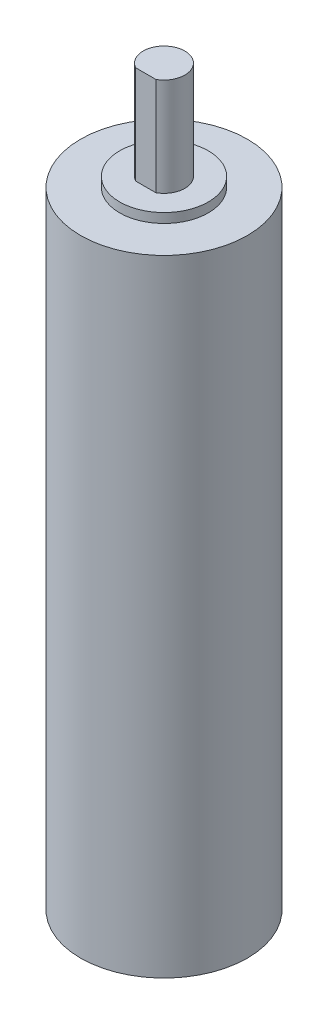
SolidWorks part; units mm, degrees
ref_plane "Front Plane" through (0, 0, 0) normal (0, 0, 1) x (1, 0, 0)
ref_plane "Top Plane" through (0, 0, 0) normal (0, 1, 0) x (1, 0, 0)
ref_plane "Right Plane" through (0, 0, 0) normal (1, 0, 0) x (0, 0, -1)
sketch "Sketch1" plane through (0, 0, 0) normal (0, 1, 0) x (1, 0, 0)
  circle A0 centre (0, 0) radius 16
extrude "Boss-Extrude1" add sketch "Sketch1" along normal blind 120
sketch "Sketch2" plane through (0, 120, 0) normal (0, 1, 0) x (1, 0, 0)
  circle A0 centre (0, 0) radius 8.5
extrude "Boss-Extrude2" add sketch "Sketch2" along normal blind 1.82
sketch "Sketch3" plane through (0, 121.82, 0) normal (0, 1, 0) x (1, 0, 0)
  line L0 (-1.9365, -3.5) -> (1.9365, -3.5)
  arc A0 (1.9365, -3.5) -> (-1.9365, -3.5) centre (0, 0) ccw
  dimension "D1" = 3.5
  dimension "D2" = 8
extrude "Boss-Extrude3" add sketch "Sketch3" along normal blind 18.82
